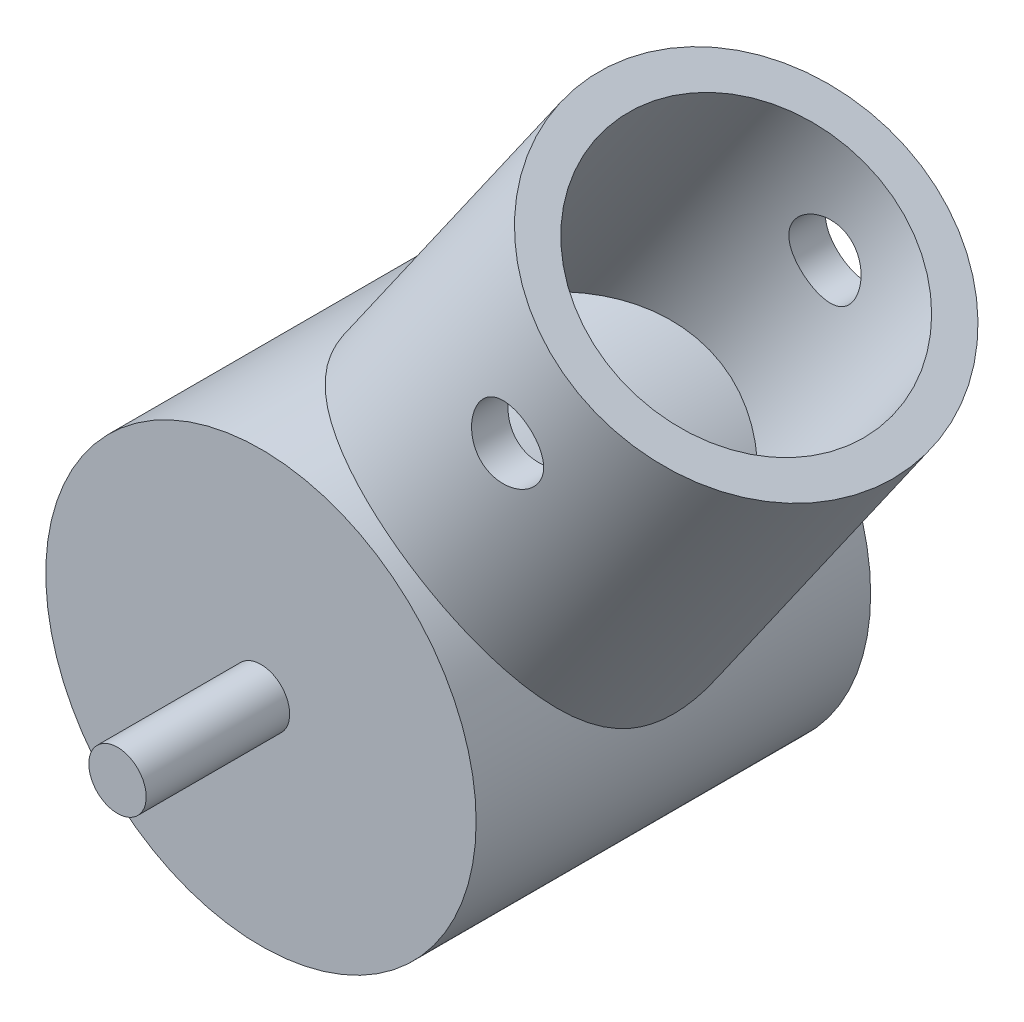
SolidWorks part; units mm, degrees
ref_plane "Front Plane" through (0, 0, 0) normal (0, 0, 1) x (1, 0, 0)
ref_plane "Top Plane" through (0, 0, 0) normal (0, 1, 0) x (1, 0, 0)
ref_plane "Right Plane" through (0, 0, 0) normal (1, 0, 0) x (0, 0, -1)
sketch "Sketch1" plane through (0, 0, 0) normal (0, 0, 1) x (1, 0, 0)
  circle A1 centre (0, 0) radius 30
  dimension "D1" = 60
extrude "Boss-Extrude1" add sketch "Sketch1" along normal mid plane 55
sketch "Sketch2" plane through (0, 0, 0) normal (0, 0, 1) x (1, 0, 0)
  line L0 (0, 0) -> (40.1504, 57.3406) construction
  line L1 (40.1504, 57.3406) -> (40.1504, 0) construction
  line L2 (40.1504, 0) -> (0, 0) construction
  line L3 (40.1504, 57.3406) -> (60.6292, 43.0012) construction
  line L4 (56.5334, 45.8691) -> (60.6292, 43.0012)
  line L5 (60.6292, 43.0012) -> (28.5089, -2.8713)
  line L6 (28.5089, -2.8713) -> (24.4131, -0.0034)
  line L7 (24.4131, -0.0034) -> (56.5334, 45.8691)
  circle A0 centre (31.5467, 45.0534) radius 5
  dimension "D3" = 10
  dimension "D1" = 35
  dimension "D2" = 70
  dimension "D4" = 15
  dimension "D5" = 20
  dimension "D6" = 5
  dimension "D7" = 56
revolve "Revolve2" add sketch "Sketch2" angle 360 about L0
sketch "Sketch3" plane through (0, 0, 0) normal (0, 0, 1) x (1, 0, 0)
  line L0 (0, 0) -> (40.1504, 57.3406) construction
  line L1 (56.5334, 45.8691) -> (23.7673, 68.8122) construction
  circle A0 centre (31.5467, 45.0534) radius 5
  dimension "D1" = 10
  dimension "D2" = 15
extrude "Cut-Extrude1" cut sketch "Sketch3" against normal mid plane 60
sketch "Sketch5" plane through (0, 0, 27.5) normal (0, 0, 1) x (1, 0, 0)
  circle A0 centre (0, 0) radius 4
  dimension "D1" = 8
extrude "Boss-Extrude2" add sketch "Sketch5" along normal blind 20
